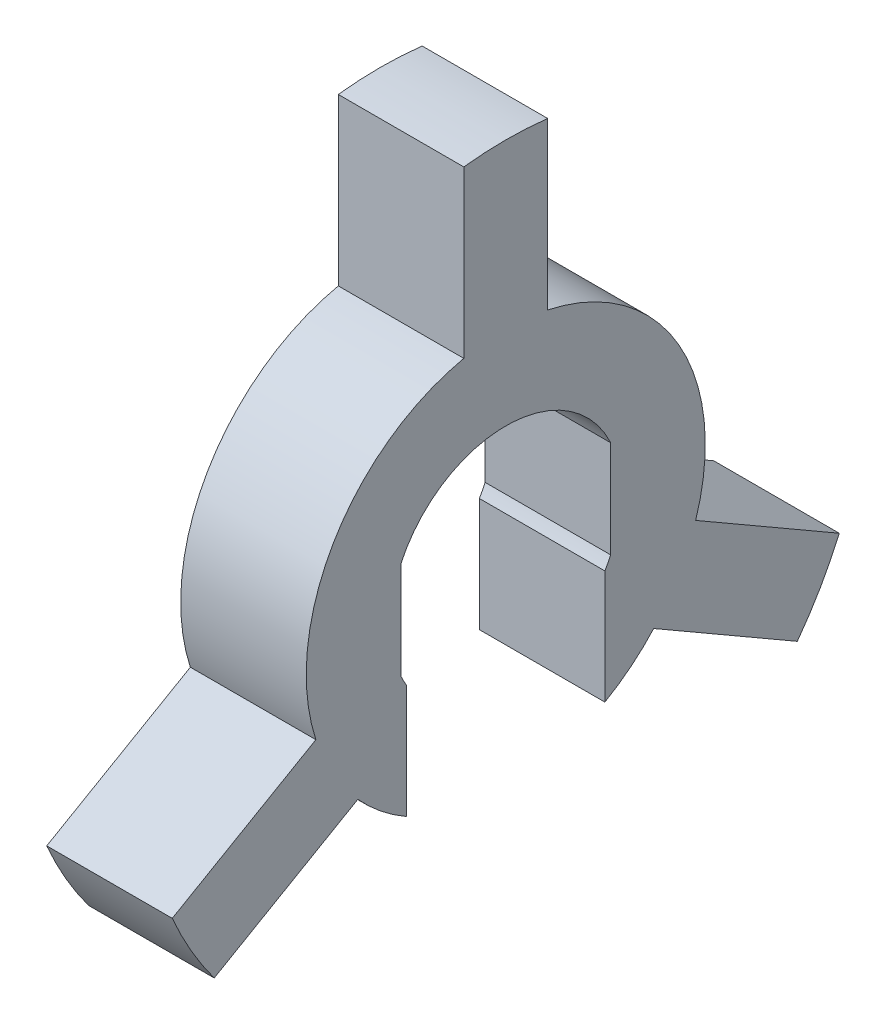
SolidWorks part; units mm, degrees
ref_plane "Frontal Plane" through (0, 0, 0) normal (0, 0, 1) x (1, 0, 0)
ref_plane "Horizontal Plane" through (0, 0, 0) normal (0, 1, 0) x (1, 0, 0)
ref_plane "Profile Plane" through (0, 0, 0) normal (1, 0, 0) x (0, 0, -1)
sketch "Sketch1" plane through (0, 0, 0) normal (1, 0, 0) x (0, 0, -1)
  line L0 (15.8817, 7.35) -> (15.8817, -7.35)
  line L1 (-15.8817, 7.35) -> (-15.8817, -7.35)
  line L2 (-15, -9.0139) -> (-15, -26.2114)
  line L3 (15, -9.0139) -> (15, -26.2114)
  line L4 (-26.154, 15.1) -> (26.154, 15.1) construction
  line L5 (26.154, 15.1) -> (0, -30.2) construction
  line L6 (0, -30.2) -> (-26.154, 15.1) construction
  line L7 (0, 0) -> (-47.6236, -27.4955) construction
  line L8 (0, 0) -> (47.6236, -27.4955) construction
  line L9 (0, 0) -> (0, 54.991) construction
  line L10 (-6.35, 54.6231) -> (-6.35, 29.5249)
  line L11 (6.35, 54.6231) -> (6.35, 29.5249)
  line L12 (50.48, -21.8123) -> (28.7443, -9.2632)
  line L13 (44.13, -32.8108) -> (22.3943, -20.2617)
  line L14 (-44.13, -32.8108) -> (-22.3943, -20.2617)
  line L15 (-50.48, -21.8123) -> (-28.7443, -9.2632)
  arc A0 (15, -26.2114) -> (22.3943, -20.2617) centre (0, 0) ccw
  arc A1 (15, -9.0139) -> (15.8817, -7.35) centre (0, 0) ccw
  arc A2 (-15.8817, -7.35) -> (-15, -9.0139) centre (0, 0) ccw
  arc A3 (15.8817, 7.35) -> (-15.8817, 7.35) centre (0, 0) ccw
  circle A4 centre (0, 0) radius 30.2 construction
  arc A6 (6.35, 54.6231) -> (-6.35, 54.6231) centre (0, 0) ccw
  arc A7 (-6.35, 29.5249) -> (-28.7443, -9.2632) centre (0, 0) ccw
  arc A8 (44.13, -32.8108) -> (50.48, -21.8123) centre (0, 0) ccw
  arc A9 (-50.48, -21.8123) -> (-44.13, -32.8108) centre (0, 0) ccw
  arc A10 (-22.3943, -20.2617) -> (-15, -26.2114) centre (0, 0) ccw
  arc A11 (28.7443, -9.2632) -> (6.35, 29.5249) centre (0, 0) ccw
  point P12 (15, -17.6127)
  point P32 (0, 0)
  dimension "D1" = 35
  dimension "D2" = 12.7
  dimension "D3" = 14.7
  dimension "D4" = 30
  dimension "D5" = 54.991
  dimension "D6" = 12.7
  dimension "D7" = 3
extrude "Boss-Extrude1" add sketch "Sketch1" along normal blind 19
equation "\"D5@Sketch1\"=4.33in/2"
